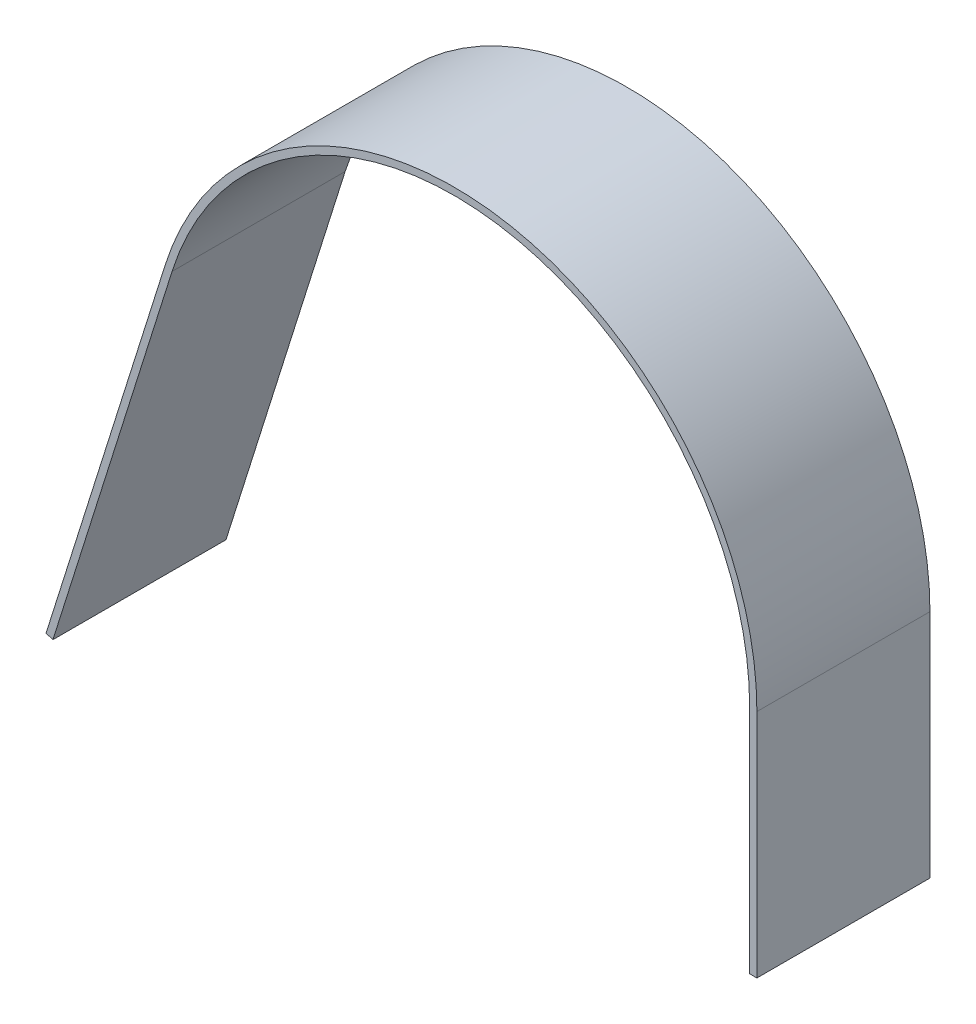
SolidWorks part; units mm, degrees
ref_plane "Front Plane" through (0, 0, 0) normal (0, 0, 1) x (1, 0, 0)
ref_plane "Top Plane" through (0, 0, 0) normal (0, 1, 0) x (1, 0, 0)
ref_plane "Right Plane" through (0, 0, 0) normal (1, 0, 0) x (0, 0, -1)
sketch "Sketch2" plane through (0, 0, 0) normal (0, 0, 1) x (1, 0, 0)
  line L0 (0, 0) -> (0, 101.6)
  line L1 (0, 101.6) -> (-133.35, 101.6) construction
  line L2 (-260.5469, 141.6395) -> (-313.0114, -25.029)
  line L3 (0, 0) -> (-3.175, 0)
  line L4 (-3.175, 0) -> (-3.175, 101.6)
  line L5 (-260.5469, 141.6395) -> (-233.4441, 133.1079) construction
  line L6 (-257.5184, 140.6862) -> (-309.9829, -25.9823)
  line L7 (-313.0114, -25.029) -> (-309.9829, -25.9823)
  arc A0 (0, 101.6) -> (-260.5469, 141.6395) centre (-133.35, 101.6) ccw
  arc A1 (-3.175, 101.6) -> (-257.5184, 140.6862) centre (-133.35, 101.6) ccw
  point P10 (-205.6026, 164.9451)
  point P11 (-210.6318, 156.9981)
  point P13 (-253.1185, 152.6005)
  point P14 (-254.5261, 149.1594)
  point P15 (-257.5184, 140.6862)
  dimension "D1" = 101.6
  dimension "D2" = 133.35
  dimension "D3" = 3.175
extrude "Boss-Extrude1" add sketch "Sketch2" along normal blind 76.2
